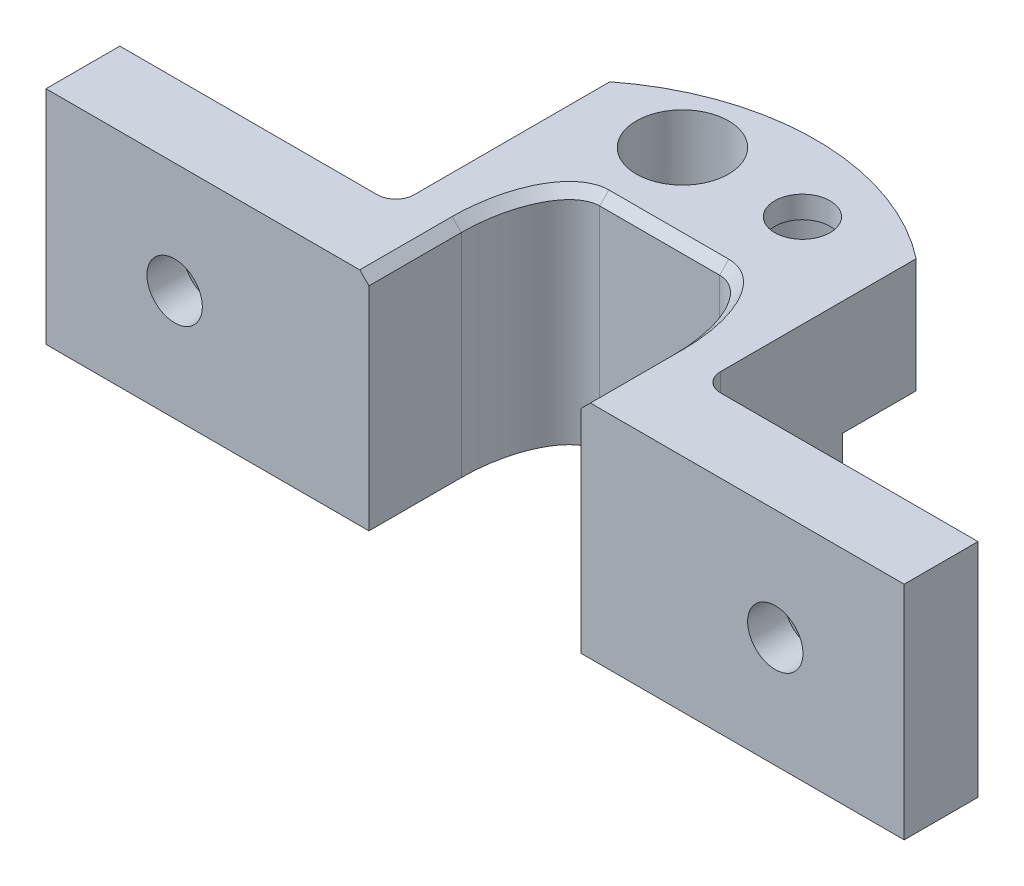
SolidWorks part; units mm, degrees
ref_plane "Front Plane" through (0, 0, 0) normal (0, 0, 1) x (1, 0, 0)
ref_plane "Top Plane" through (0, 0, 0) normal (0, 1, 0) x (1, 0, 0)
ref_plane "Right Plane" through (0, 0, 0) normal (1, 0, 0) x (0, 0, -1)
sketch "Sketch1" plane through (0, 0, 0) normal (0, 1, 0) x (1, 0, 0)
  line L0 (-3.25, -5) -> (-23.25, -5)
  line L1 (-3.25, -5) -> (3.25, -5) construction
  line L2 (-3.25, -5) -> (-3.25, 5) construction
  line L3 (-3.25, 5) -> (3.25, 5)
  line L4 (3.25, -5) -> (3.25, 5) construction
  line L5 (-3.25, -5) -> (3.25, 5) construction
  line L6 (-3.25, 5) -> (3.25, -5) construction
  line L7 (-23.25, -5) -> (-23.25, -1)
  line L8 (-23.25, -1) -> (-9.3, -1)
  line L9 (3.25, -5) -> (23.25, -5)
  line L10 (23.25, -5) -> (23.25, -3)
  line L12 (-8.3, 0) -> (-8.3, 6.6)
  line L13 (-8.3, 6.6) -> (8.3, 6.6)
  line L14 (8.3, 0) -> (8.3, 6.6)
  line L15 (-5.7498, 0) -> (-5.7498, -5)
  line L16 (5.7487, 0) -> (5.7487, -5)
  line L17 (23.25, -3) -> (23.25, -1)
  line L18 (23.25, -1) -> (9.3, -1)
  arc A0 (-9.3, -1) -> (-8.3, 0) centre (-9.3, 0) ccw
  arc A1 (9.3, -1) -> (8.3, 0) centre (9.3, 0) cw
  ellipse E0 centre (-3.25, 0) end of major axis (-3.25, 5) minor radius 2.4998 (-3.25, 5) -> (-3.25, -5) ccw
  ellipse E1 centre (3.25, 0) end of major axis (3.25, 5) minor radius 2.4987 (3.25, -5) -> (3.25, 5) ccw
  point P0 (0, 0)
  dimension "D6" = 1
  dimension "D7" = 4
  dimension "D12" = 1
  dimension "D1" = 6.5
  dimension "D2" = 10
  dimension "D3" = 20
  dimension "D4" = 4
  dimension "D5" = 20
  dimension "D8" = 16.6
  dimension "D9" = 1.6
  dimension "D10" = 5.05
  dimension "D11" = 5.05
extrude "Boss-Extrude1" add sketch "Sketch1" along normal blind 12
sketch "Sketch2" plane through (0, 0, 1) normal (0, 0, -1) x (-1, 0, 0)
  line L0 (-23.25, 12) -> (-9.2822, 0) construction
  line L1 (-23.25, 0) -> (-9.2822, 12) construction
  line L2 (23.25, 12) -> (9.3079, 0) construction
  line L3 (23.25, 0) -> (9.3, 0) construction
  line L4 (23.25, 0) -> (9.2822, 12) construction
  line L5 (-16.2661, 6) -> (-16.2661, -2.9743) construction
  line L6 (-16.2661, -0.7517) -> (-16.2661, 3) construction
  line L10 (16.2789, 6) -> (16.2789, -2.9743) construction
  line L11 (19.8585, 6) -> (18.0687, 9.1)
  line L12 (-12.6865, 6) -> (-14.4763, 9.1)
  line L13 (-14.4763, 9.1) -> (-18.0559, 9.1)
  line L14 (-18.0559, 9.1) -> (-19.8457, 6)
  line L15 (-19.8457, 6) -> (-18.0559, 2.9)
  line L16 (18.0687, 9.1) -> (14.4891, 9.1)
  line L17 (14.4891, 9.1) -> (12.6994, 6)
  line L18 (-18.0559, 2.9) -> (-14.4763, 2.9)
  line L19 (-14.4763, 2.9) -> (-12.6865, 6)
  line L20 (12.6994, 6) -> (14.4891, 2.9)
  line L21 (14.4891, 2.9) -> (18.0687, 2.9)
  line L22 (18.0687, 2.9) -> (19.8585, 6)
  circle A0 centre (-16.2661, 6) radius 3.1 construction
  circle A1 centre (16.2789, 6) radius 3.1 construction
  point P32 (11.4039, 0.6926)
  dimension "D1" = 6.2
  dimension "D2" = 6.2
extrude "Cut-Extrude1" cut sketch "Sketch2" against normal blind 2
sketch "Sketch3" plane through (0, 12, 0) normal (0, 1, 0) x (1, 0, 0)
  line L0 (-3.25, 5) -> (-3.25, 12.9854) construction
  line L1 (3.25, 5) -> (3.25, 12.9854) construction
  line L2 (-8.3, 6.6) -> (8.3, 6.6)
  line L3 (-8.1382, 9.4853) -> (3.25, 9.4853) construction
  line L4 (8.3, 6.6) -> (8.3, 10.6)
  line L5 (-8.3, 6.6) -> (-8.3, 10.6)
  circle A0 centre (-3.25, 9.4853) radius 2.5
  circle A1 centre (3.25, 9.4853) radius 2.5 construction
  circle A2 centre (3.25, 9.4853) radius 1.5
  circle A3 centre (0, 0) radius 13.8 construction
  circle A4 centre (-3.25, 9.4853) radius 2.85 construction
  circle A5 centre (3.25, 9.4853) radius 2.85 construction
  arc A6 (8.3, 10.6) -> (-8.3, 10.6) centre (0, 0) ccw
  circle A7 centre (0, 0) radius 13 construction
  ellipse E5 centre (-3.5001, 0.0027) end of major axis (-3.5004, -7) minor radius 5 (-3.1436, 6.9875) -> (-3.5619, 7.0048) ccw
  dimension "D1" = 5
  dimension "D2" = 3
  dimension "D3" = 27.6
  dimension "D4" = 5.7
  dimension "D5" = 5.7
  dimension "D8" = 13.4629
  dimension "D9" = 26
  dimension "D6" = 4
  dimension "D7" = 4
extrude "Boss-Extrude2" add sketch "Sketch3" against normal blind 1.2
sketch "Sketch4" plane through (0, 10.8, 0) normal (0, -1, 0) x (1, 0, 0)
  line L0 (-8.3, -6.6) -> (8.3, -6.6)
  line L1 (8.3, -6.6) -> (8.3, -10.6)
  line L2 (-8.3, -6.6) -> (-8.3, -10.6)
  line L3 (-3.25, -9.4853) -> (3.25, -9.4853) construction
  line L4 (0, -7.2638) -> (0, -12.3361) construction
  circle A0 centre (-3.25, -9.4853) radius 2.5
  circle A1 centre (3.25, -9.4853) radius 2.5
  ellipse E1 centre (0, -10.6) end of major axis (8.3, -10.6) minor radius 3.3362 (-8.3, -10.6) -> (8.3, -10.6) ccw
  dimension "D1" = 5
  dimension "D2" = 5
extrude "Boss-Extrude3" add sketch "Sketch4" along normal blind 5
chamfer "Chamfer1" distance 0.5 angle 45 5 edges at (0, 12, -5) (-5.0176, 12, -3.5355) (5.0168, 12, -3.5355) (-5.7498, 12, 2.5) (5.7487, 12, 2.5)
sketch "Sketch5" plane through (0, 0, 1) normal (0, 0, -1) x (-1, 0, 0)
  line L0 (12.6994, 6) -> (19.8585, 6) construction
  line L1 (19.8585, 6) -> (18.0687, 9.1) construction
  line L2 (19.8585, 6) -> (18.0687, 9.1) construction
  line L3 (16.2789, 9.1) -> (16.2789, 2.9) construction
  line L4 (18.0687, 9.1) -> (14.4891, 9.1) construction
  line L5 (14.4891, 2.9) -> (18.0687, 2.9) construction
  line L6 (-16.2661, 9.1) -> (-16.2661, 2.9) construction
  line L7 (-14.4763, 9.1) -> (-18.0559, 9.1) construction
  line L8 (-18.0559, 2.9) -> (-14.4763, 2.9) construction
  line L9 (-19.8457, 6) -> (-12.6865, 6) construction
  circle A0 centre (-16.2661, 6) radius 1.5
  circle A1 centre (16.2789, 6) radius 1.5
  dimension "D1" = 3
  dimension "D2" = 3
extrude "Cut-Extrude2" cut sketch "Sketch5" against normal blind 5
